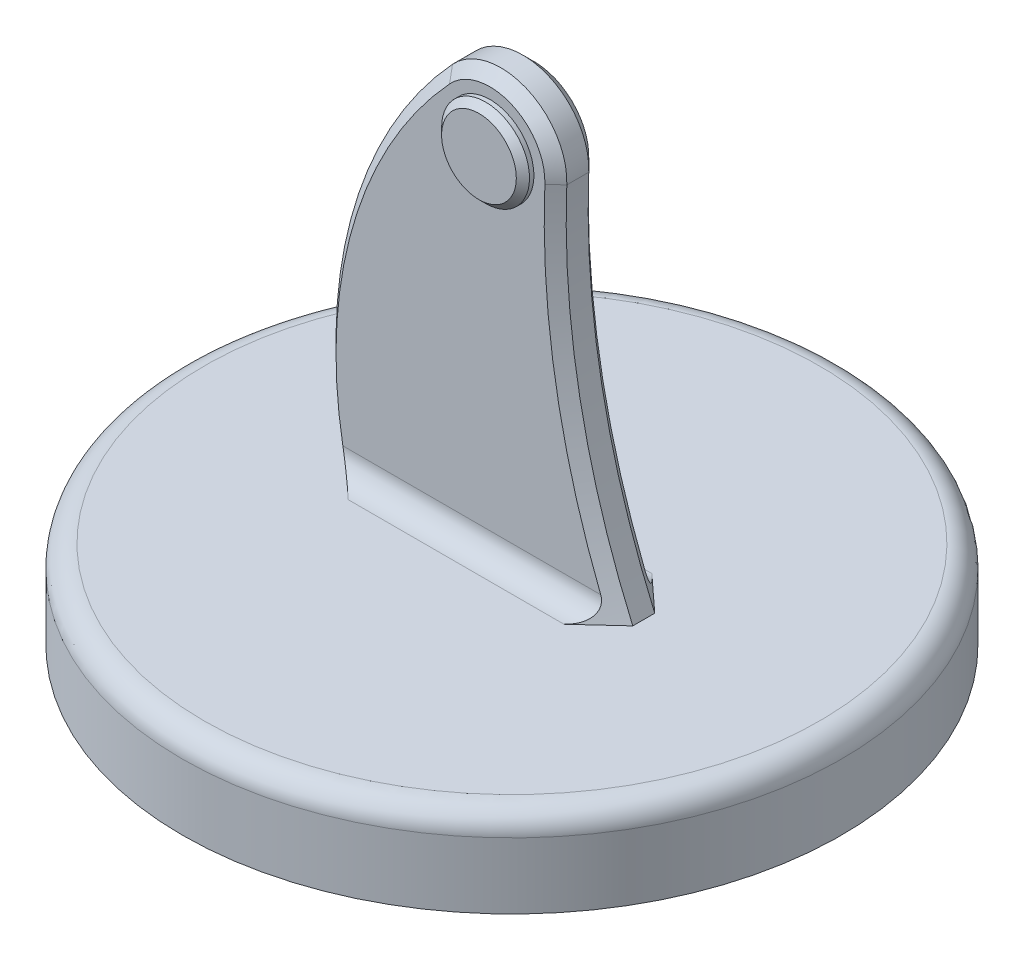
SolidWorks part; units mm, degrees
ref_plane "Front Plane" through (0, 0, 0) normal (0, 0, 1) x (1, 0, 0)
ref_plane "Top Plane" through (0, 0, 0) normal (0, 1, 0) x (1, 0, 0)
ref_plane "Right Plane" through (0, 0, 0) normal (1, 0, 0) x (0, 0, -1)
sketch "Sketch2" plane through (0, 0, 0) normal (0, 1, 0) x (1, 0, 0)
  circle A0 centre (0, 0) radius 75
  dimension "D1" = 150
extrude "Boss-Extrude1" add sketch "Sketch2" along normal blind 20
fillet "Fillet1" radius 5 1 edges at (0, 20, 75)
sketch "Sketch3" plane through (0, 0, 0) normal (0, 0, 1) x (1, 0, 0)
  line L0 (0, 0) -> (0, 100) construction
  line L1 (70, 20) -> (-70, 20) construction
  line L2 (-35, 20) -> (30, 20)
  arc A0 (14.9883, 99.4067) -> (-11.0239, 110.1722) centre (0, 100) ccw
  arc A1 (-35, 20) -> (-11.0239, 110.1722) centre (62.4687, 42.3575) cw
  arc A2 (14.9883, 99.4067) -> (30, 20) centre (194.8474, 92.2865) ccw
  dimension "D3" = 30
  dimension "D4" = 180
  dimension "D5" = 100
  dimension "D6" = 30
  dimension "D2" = 100
  dimension "D1" = 35
extrude "Boss-Extrude2" add sketch "Sketch3" along normal mid plane 10
chamfer "Chamfer14" distance 2.5 angle 45 3 edges at (-34.1734, 68.0539, -5) (5.7361, 113.8599, -5) (17.9802, 58.85, -5)
chamfer "Chamfer15" distance 2.5 angle 45 3 edges at (-34.1734, 68.0539, 5) (5.7361, 113.8599, 5) (17.9802, 58.85, 5)
fillet "Fillet4" radius 5 1 edges at (-2.5798, 20, 5)
fillet "Fillet5" radius 5 1 edges at (-2.5798, 20, -5)
sketch "Sketch4" plane through (0, 0, 5) normal (0, 0, 1) x (1, 0, 0)
  circle A0 centre (0, 100) radius 10
  dimension "D1" = 20
extrude "Boss-Extrude8" add sketch "Sketch4" along normal mid plane 5
sketch "Sketch5" plane through (0, 0, -5) normal (0, 0, -1) x (-1, 0, 0)
  circle A0 centre (0, 100) radius 5
  dimension "D1" = 10
extrude "Cut-Extrude1" cut sketch "Sketch5" against normal blind 10
chamfer "Chamfer24" distance 1.5 angle 45 1 edges at (10, 100, 7.5)
